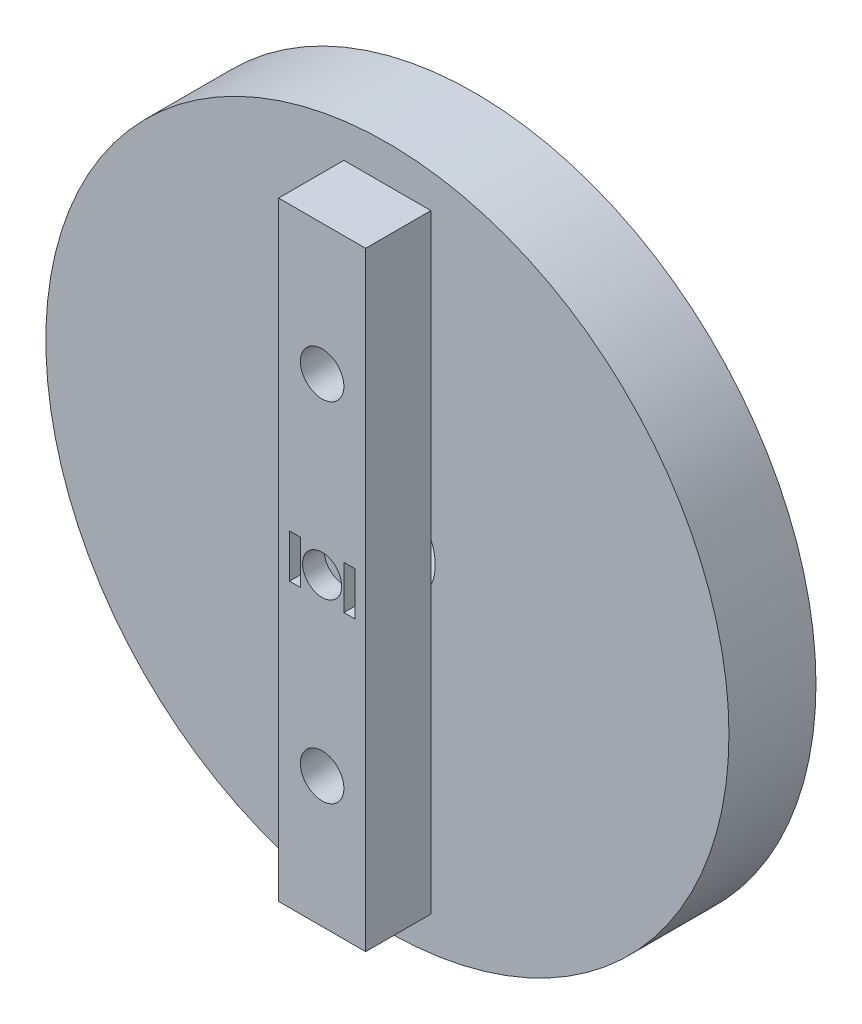
SolidWorks part; units mm, degrees
ref_plane "前视基准面" through (0, 0, 0) normal (0, 0, 1) x (1, 0, 0)
ref_plane "上视基准面" through (0, 0, 0) normal (0, 1, 0) x (1, 0, 0)
ref_plane "右视基准面" through (0, 0, 0) normal (1, 0, 0) x (0, 0, -1)
sketch "草图1" plane through (0, 0, 0) normal (0, 0, 1) x (1, 0, 0)
  circle A0 centre (0, 0) radius 15.7
extrude "凸台-拉伸1" add sketch "草图1" along normal blind 4
sketch "草图2" plane through (0, 0, 0) normal (0, 0, -1) x (-1, 0, 0)
  circle A0 centre (0, 0) radius 2.2
extrude "切除-拉伸1" cut sketch "草图2" against normal blind 4
sketch "草图3" plane through (0, 0, 4) normal (0, 0, 1) x (1, 0, 0)
  line L0 (-2, 14) -> (2, 14)
  line L1 (-2, 14) -> (-2, -14)
  line L2 (2, 14) -> (2, -14)
  line L3 (-2, -14) -> (2, -14)
extrude "凸台-拉伸2" add sketch "草图3" along normal blind 3 separate body
sketch "草图5" plane through (0, 0, 7) normal (0, 0, 1) x (1, 0, 0)
  circle A0 centre (0, 0) radius 0.9
extrude "切除-拉伸3" cut sketch "草图5" against normal blind 1
sketch "草图6" plane through (0, 0, 6) normal (0, 0, 1) x (1, 0, 0)
  circle A0 centre (0, 0) radius 0.4
extrude "切除-拉伸4" cut sketch "草图6" against normal blind 2
sketch "草图7" plane through (0, 0, 7) normal (0, 0, 1) x (1, 0, 0)
  line L4 (1, 1) -> (1, -1)
  line L5 (1, 1) -> (1.5, 1)
  line L6 (1, -1) -> (1.5, -1)
  line L7 (1.5, 1) -> (1.5, -1)
  line L8 (-1, 1) -> (-1, -1)
  line L9 (-1, 1) -> (-1.5, 1)
  line L10 (-1, -1) -> (-1.5, -1)
  line L11 (-1.5, 1) -> (-1.5, -1)
extrude "切除-拉伸5" cut sketch "草图7" against normal blind 3 contours L4 L5 L7 L6 | L8 L9 L11 L10
sketch "草图8" plane through (0, 0, 7) normal (0, 0, 1) x (1, 0, 0)
  circle A0 centre (0, 8) radius 1
  circle A1 centre (0, -8) radius 1
extrude "切除-拉伸6" cut sketch "草图8" against normal blind 5
